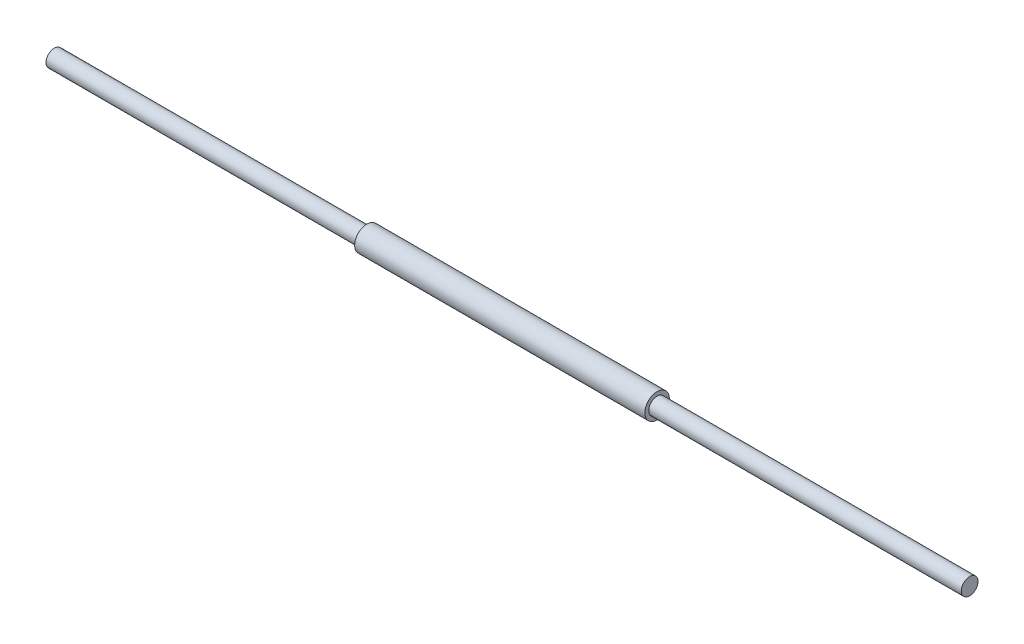
SolidWorks part; units mm, degrees
material "AISI 1020"
ref_plane "Front Plane" through (0, 0, 0) normal (0, 0, 1) x (1, 0, 0)
ref_plane "Top Plane" through (0, 0, 0) normal (0, 1, 0) x (1, 0, 0)
ref_plane "Right Plane" through (0, 0, 0) normal (1, 0, 0) x (0, 0, -1)
sketch "Sketch3" plane through (0, 0, 0) normal (0, 0, 1) x (1, 0, 0)
  line L0 (260.35, 6.985) -> (260.35, 0) construction
  line L1 (0, 0) -> (177.8, 0)
  line L2 (0, 0) -> (0, 4.7625)
  line L3 (0, 4.7625) -> (177.8, 4.7625)
  line L4 (177.8, 0) -> (177.8, 4.7625)
  line L5 (177.8, 0) -> (342.9, 0)
  line L6 (177.8, 0) -> (177.8, 6.985)
  line L7 (177.8, 6.985) -> (342.9, 6.985)
  line L8 (342.9, 0) -> (342.9, 6.985)
  line L9 (342.9, 0) -> (520.7, 0)
  line L10 (342.9, 0) -> (342.9, 4.7625)
  line L11 (342.9, 4.7625) -> (520.7, 4.7625)
  line L12 (520.7, 0) -> (520.7, 4.7625)
  dimension "D1" = 4.7625
  dimension "D2" = 4.7625
  dimension "D3" = 520.7
  dimension "D4" = 6.985
  dimension "D5" = 165.1
revolve "Revolve2" add sketch "Sketch3" angle 360 about L9
equation "\"A\"= 20.5"
equation "\"B\"= 6.5"
equation "\"C\"= 36deg"
